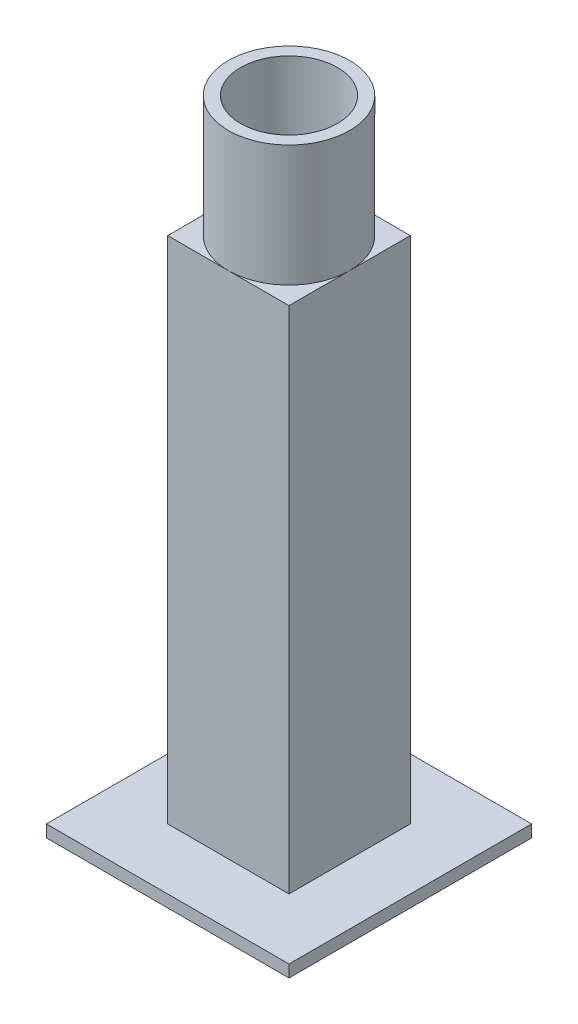
SolidWorks part; units mm, degrees
ref_plane "Front Plane" through (0, 0, 0) normal (0, 0, 1) x (1, 0, 0)
ref_plane "Top Plane" through (0, 0, 0) normal (0, 1, 0) x (1, 0, 0)
ref_plane "Right Plane" through (0, 0, 0) normal (1, 0, 0) x (0, 0, -1)
sketch "Sketch1" plane through (0, 0, 0) normal (0, 1, 0) x (1, 0, 0)
  line L1 (0, 0) -> (200, 0)
  line L2 (0, 0) -> (0, 200)
  line L3 (0, 200) -> (200, 200)
  line L4 (200, 0) -> (200, 200)
  dimension "D1" = 200
  dimension "D2" = 200
extrude "Boss-Extrude1" add sketch "Sketch1" along normal blind 10
sketch "Sketch2" plane through (0, 10, 0) normal (0, 1, 0) x (1, 0, 0)
  line L0 (200, 200) -> (0, 200) construction
  line L1 (50, 150) -> (150, 150)
  line L2 (50, 150) -> (50, 50)
  line L3 (50, 50) -> (150, 50)
  line L4 (150, 150) -> (150, 50)
  line L6 (0, 200) -> (0, 0) construction
  dimension "D1" = 100
  dimension "D2" = 100
  dimension "D3" = 50
  dimension "D4" = 50
extrude "Boss-Extrude2" add sketch "Sketch2" along normal blind 420
sketch "Sketch3" plane through (0, 430, 0) normal (0, 1, 0) x (1, 0, 0)
  line L0 (50, 150) -> (50, 50) construction
  line L1 (50, 50) -> (150, 50) construction
  circle A0 centre (100, 100) radius 40
  dimension "D1" = 80
  dimension "D2" = 50
  dimension "D3" = 50
extrude "Cut-Extrude1" cut sketch "Sketch3" against normal blind 420
sketch "Sketch5" plane through (0, 430, 0) normal (0, 1, 0) x (1, 0, 0)
  circle A0 centre (100, 100) radius 50
  circle A1 centre (100, 100) radius 40
  dimension "D1" = 100
  dimension "D2" = 80
extrude "Boss-Extrude4" add sketch "Sketch5" along normal blind 100
